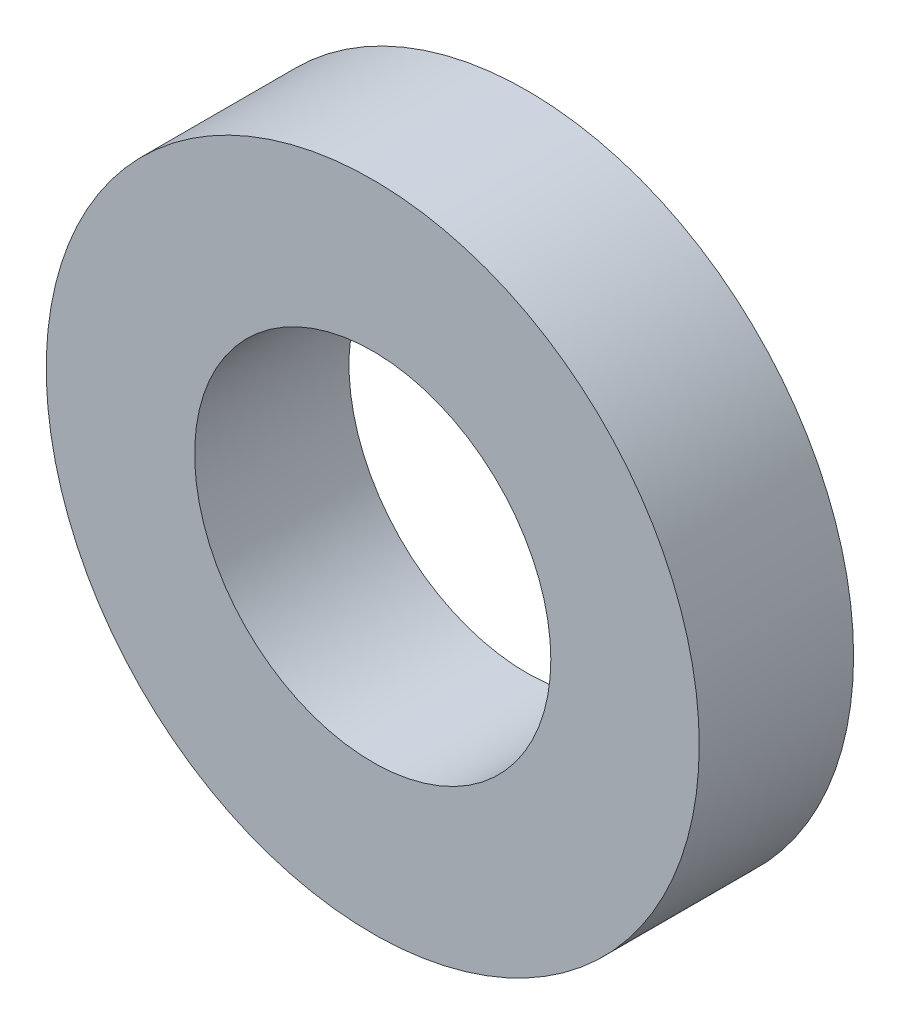
SolidWorks part; units mm, degrees
material "Custom Plastic"
ref_plane "X-Y Datum" through (0, 0, 0) normal (0, 0, 1) x (1, 0, 0)
ref_plane "X-Z Datum" through (0, 0, 0) normal (0, 1, 0) x (1, 0, 0)
ref_plane "Y-Z Datum" through (0, 0, 0) normal (1, 0, 0) x (0, 0, -1)
sketch "Sketch1" plane through (0, 0, 0) normal (1, 0, 0) x (0, 0, -1)
  line L0 (0, 0) -> (50.8909, 0) construction
  line L6 (0, 27.5) -> (13, 27.5)
  line L7 (0, 27.5) -> (0, 15)
  line L8 (0, 15) -> (13, 15)
  line L9 (13, 27.5) -> (13, 15)
  dimension "D1" = 15
  dimension "D2" = 27.5
  dimension "D3" = 13
  dimension "D4" = 13
revolve "Revolve1" add sketch "Sketch1" angle 360 about L0
